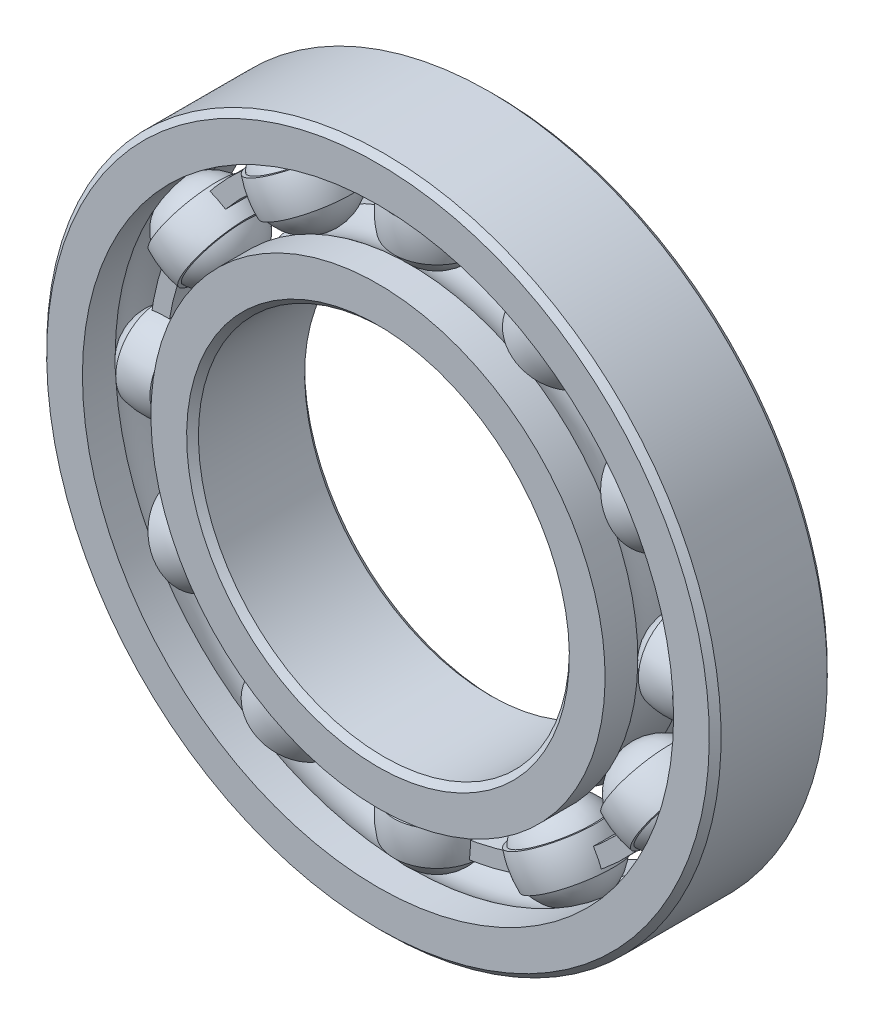
SolidWorks part; units mm, degrees
ref_plane "Front Plane" through (0, 0, 0) normal (0, 0, 1) x (1, 0, 0)
ref_plane "Top Plane" through (0, 0, 0) normal (0, 1, 0) x (1, 0, 0)
ref_plane "Right Plane" through (0, 0, 0) normal (1, 0, 0) x (0, 0, -1)
sketch "Sketch1" plane through (0, 0, 0) normal (0, 0, 1) x (1, 0, 0)
  line L0 (-31.75, 0) -> (31.75, 0) construction
  line L1 (-17.4625, 0) -> (17.4625, 0) construction
  circle A0 centre (0, 0) radius 17.4625 construction
  circle A1 centre (0, 0) radius 31.75 construction
  point P3 (0, 0)
  point P6 (0, 0)
  point P7 (0, -17.4625)
  point P11 (0, -31.75)
  point P12 (0, 17.4625)
  point P13 (0, 31.75)
  dimension "OD" = 63.5
  dimension "ID" = 34.925
sketch "SketchB" plane through (0, 0, 0) normal (1, 0, 0) x (0, 0, -1)
  line L0 (-5.5563, 31.75) -> (5.5562, 31.75) construction
  line L1 (0, 31.75) -> (0, -31.75) construction
  line L2 (5.0006, 31.75) -> (-5.0006, 31.75)
  line L3 (-5.0006, 31.75) -> (-5.5563, 31.1944)
  line L4 (-5.5563, 31.1944) -> (-5.5563, 27.8301)
  line L5 (-5.5563, 27.8301) -> (-2.4694, 27.8301)
  line L6 (5.5562, 27.8301) -> (2.4694, 27.8301)
  line L7 (5.5562, 31.1944) -> (5.5562, 27.8301)
  line L8 (5.0006, 31.75) -> (5.5562, 31.1944)
  line L9 (0, 31.75) -> (0, 24.6062) construction
  line L10 (0, 24.6062) -> (0, 17.4625) construction
  line L11 (0, 31.75) -> (0, -31.75) construction
  line L12 (-5.5562, 0) -> (5.5562, 0) construction
  line L13 (5.5562, 17.4625) -> (-5.5563, 17.4625) construction
  line L14 (0, 28.6672) -> (0, 20.5453) construction
  line L15 (-5.5562, -17.4625) -> (5.5563, -17.4625) construction
  arc A0 (-2.4694, 27.8301) -> (2.4694, 27.8301) centre (0, 24.6062) cw
  circle A1 centre (0, 24.6062) radius 4.061 construction
  point P14 (0, 17.4625)
  point P17 (0, 0)
  point P21 (0, 31.75)
  point P29 (0, 17.4625)
  point P30 (0, -17.4625)
  point P35 (0, 28.6672)
  dimension "Width" = 11.1125
  dimension "D1" = 45
  dimension "D2" = 0.5556
  dimension "D3" = 4.9389
  dimension "D4" = 3.2238
sketch "Sketch7" plane through (0, 0, 0) normal (1, 0, 0) x (0, 0, -1)
  line L0 (5.0006, 31.75) -> (5.5562, 31.1944) construction
  line L1 (5.5562, 31.1944) -> (5.5562, 27.8301) construction
  line L2 (5.5562, 27.8301) -> (2.4694, 27.8301) construction
  line L3 (-5.5563, 27.8301) -> (-2.4694, 27.8301) construction
  line L4 (-5.5563, 31.1944) -> (-5.5563, 27.8301) construction
  line L5 (-5.0006, 31.75) -> (-5.5563, 31.1944) construction
  line L6 (5.0006, 31.75) -> (-5.0006, 31.75) construction
  line L7 (5.0006, 31.75) -> (5.5562, 31.1944)
  line L8 (5.5562, 31.1944) -> (5.5562, 27.8301)
  line L9 (5.5562, 27.8301) -> (2.4694, 27.8301)
  line L10 (-5.5563, 27.8301) -> (-2.4694, 27.8301)
  line L11 (-5.5563, 31.1944) -> (-5.5563, 27.8301)
  line L12 (-5.0006, 31.75) -> (-5.5563, 31.1944)
  line L13 (5.0006, 31.75) -> (-5.0006, 31.75)
  arc A0 (2.4694, 27.8301) -> (-2.4694, 27.8301) centre (0, 24.6062) ccw construction
  arc A1 (2.4694, 27.8301) -> (-2.4694, 27.8301) centre (0, 24.6062) ccw
revolve "Revolve6" add sketch "Sketch7" angle 360 about L12
sketch "Sketch3" plane through (0, 0, 0) normal (1, 0, 0) x (0, 0, -1)
  line L0 (0, 31.75) -> (0, -31.75) construction
  line L1 (0, 31.75) -> (0, -31.75) construction
  line L2 (-5.0006, 17.4625) -> (-5.5563, 18.0181)
  line L3 (-5.5563, 18.0181) -> (-5.5563, 21.3824)
  line L5 (-5.5563, 21.3824) -> (-2.4694, 21.3824)
  line L6 (-5.0006, 17.4625) -> (5.0006, 17.4625)
  line L8 (5.0006, 17.4625) -> (5.5563, 18.0181)
  line L10 (5.5563, 18.0181) -> (5.5563, 21.3824)
  line L11 (5.5563, 21.3824) -> (2.4694, 21.3824)
  line L12 (-5.5563, 31.1944) -> (-5.5563, 27.8301) construction
  line L13 (5.0006, 31.75) -> (5.5562, 31.1944) construction
  line L15 (5.5563, -31.1944) -> (5.5563, 31.1944) construction
  line L16 (5.0006, 31.75) -> (5.0006, -31.75) construction
  arc A1 (2.4694, 21.3824) -> (-2.4694, 21.3824) centre (0, 24.6062) cw
  circle A2 centre (0, 24.6062) radius 4.061 construction
  point P1 (0, 17.4625)
revolve "Revolve3" add sketch "Sketch3" angle 360 about L12
sketch "Sketch4" plane through (0, 0, 0) normal (1, 0, 0) x (0, 0, -1)
  line L0 (-4.061, 24.6062) -> (4.061, 24.6062)
  arc A2 (-4.061, 24.6062) -> (4.061, 24.6062) centre (0, 24.6062) cw
  arc A3 (2.4694, 27.8301) -> (-2.4694, 27.8301) centre (0, 24.6062) ccw construction
revolve "Revolve4" add sketch "Sketch4" angle 360 about L0
sketch "Sketch8" plane through (0, 0, 0) normal (1, 0, 0) x (0, 0, -1)
  line L0 (-2.4694, 27.8301) -> (-2.4694, 26.2182) construction
  line L1 (-2.4694, 26.2182) -> (-2.4694, 24.6062) construction
  line L2 (-2.4694, 24.6062) -> (-2.4694, 22.9943) construction
  line L3 (-2.4694, 22.9943) -> (-2.4694, 21.3824) construction
  line L4 (-5.5563, 26.2182) -> (-5.2514, 26.2182) construction
  line L5 (-2.4694, 26.2182) -> (-2.4694, 22.9943) construction
  line L7 (-5.2514, 26.2182) -> (-4.9466, 26.2182) construction
  line L8 (-4.9466, 26.2182) -> (-4.6418, 26.2182) construction
  line L10 (0, 31.75) -> (0, -31.75) construction
  line L11 (0, 31.75) -> (0, -31.75) construction
  line L12 (-5.5563, 27.8301) -> (-5.5563, 26.2182) construction
  line L13 (-4.0322, 26.2182) -> (-3.7273, 26.2182) construction
  line L14 (-5.5563, 31.1944) -> (-5.5563, -31.1944) construction
  line L15 (-5.5563, 26.2182) -> (-5.5563, 24.6062) construction
  line L16 (-5.5563, 24.6062) -> (-5.5563, 22.9943) construction
  line L17 (-5.5563, 22.9943) -> (-5.5563, 21.3824) construction
  line L18 (-4.6418, 26.2182) -> (-4.337, 26.2182) construction
  line L19 (-4.337, 26.2182) -> (-4.0322, 26.2182) construction
  line L20 (-3.7273, 26.2182) -> (-4.0322, 26.2182)
  line L21 (-5.5563, 22.9943) -> (-5.2514, 22.9943) construction
  line L22 (-5.2514, 22.9943) -> (-4.9466, 22.9943) construction
  line L23 (-4.9466, 22.9943) -> (-4.6418, 22.9943) construction
  line L24 (-4.6418, 22.9943) -> (-4.337, 22.9943) construction
  line L25 (-4.337, 22.9943) -> (-4.0322, 22.9943) construction
  line L26 (-4.0322, 22.9943) -> (-3.7273, 22.9943) construction
  line L27 (-3.7273, 22.9943) -> (-4.0322, 22.9943)
  line L28 (-4.337, 26.2182) -> (-4.337, 22.9943) construction
  line L30 (-4.1846, 26.2182) -> (-4.1846, 22.9943) construction
  circle A0 centre (0, 24.6062) radius 4.061 construction
  arc A2 (-4.0322, 22.9943) -> (-4.0322, 26.2182) centre (4.4157, 24.6062) cw
  arc A3 (-3.7273, 26.2182) -> (-3.7273, 22.9943) centre (0, 24.6062) ccw
revolve "Revolve7" add sketch "Sketch8" angle 360 about L11
pattern_circular "CirPattern1" count 12 over 360 about axis through (0, 0, 0) along (0, 0, 1) of bodies 134 104
sketch "Sketch9" plane through (0, 0, 0) normal (0, 0, 1) x (1, 0, 0)
  line L0 (0, 21.3824) -> (0, 22.457) construction
  line L1 (0, 20.5453) -> (0, 28.6672) construction
  line L2 (0, 22.457) -> (0, 23.5316) construction
  line L3 (0, 23.5316) -> (0, 24.6062) construction
  line L4 (0, 24.6062) -> (0, 25.6809) construction
  line L5 (0, 25.6809) -> (0, 26.7555) construction
  line L6 (0, 26.7555) -> (0, 27.8301) construction
  line L7 (0, 31.1944) -> (0, 27.8301) construction
  line L8 (0, 31.75) -> (0, -31.75) construction
  circle A0 centre (0, 0) radius 21.3824 construction
  circle A1 centre (0, 0) radius 24.6062
  circle A2 centre (0, 0) radius 26.2182
  point P19 (0, 26.2182)
extrude "Boss-Extrude1" add sketch "Sketch9" along normal mid plane 1.8521 separate body
equation "\"D2@SketchB\" = \"Width@SketchB\" * .05"
equation "\"D3@SketchB\" = \"Width@SketchB\" / 2.25"
equation "\"D4@SketchB\" =  (  (  ( \"OD@Sketch1\" - \"Width@SketchB\" )  / 2 )  / 3.25 )  / 2.5"
equation "\"D1@Boss-Extrude1\"=\"Width@SketchB\"/6"
